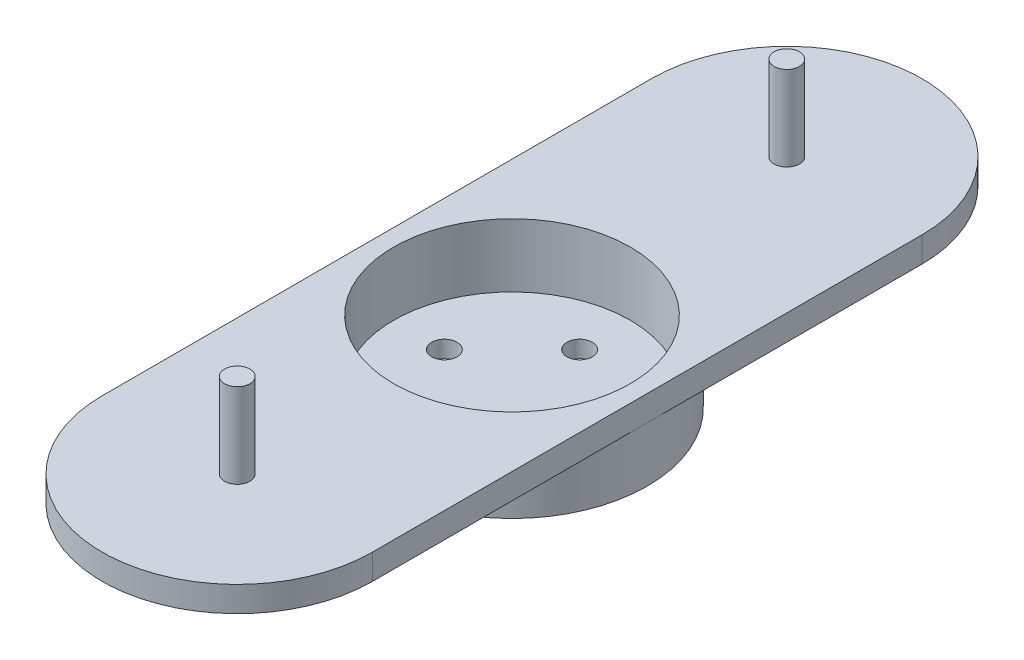
SolidWorks part; units mm, degrees
ref_plane "前视基准面" through (0, 0, 0) normal (0, 0, 1) x (1, 0, 0)
ref_plane "上视基准面" through (0, 0, 0) normal (0, 1, 0) x (1, 0, 0)
ref_plane "右视基准面" through (0, 0, 0) normal (1, 0, 0) x (0, 0, -1)
sketch "Sketch1" plane through (0, 0, 0) normal (0, 1, 0) x (1, 0, 0)
  circle A0 centre (0, 0) radius 16
  dimension "D1" = 32
extrude "Boss-Extrude1" add sketch "Sketch1" along normal blind 6.5
sketch "Sketch2" plane through (0, 6.5, 0) normal (0, 1, 0) x (1, 0, 0)
  line L0 (0, -32.5) -> (0, 32.5) construction
  line L1 (-16, -32.5) -> (-16, 32.5)
  line L2 (16, -32.5) -> (16, 32.5)
  arc A0 (-16, -32.5) -> (16, -32.5) centre (0, -32.5) ccw
  arc A1 (16, 32.5) -> (-16, 32.5) centre (0, 32.5) ccw
  circle A2 centre (0, 0) radius 16 construction
  point P2 (0, 0)
  dimension "D1" = 65
extrude "Boss-Extrude2" add sketch "Sketch2" along normal blind 3
sketch "Sketch3" plane through (0, 9.5, 0) normal (0, 1, 0) x (1, 0, 0)
  circle A0 centre (0, 32.5) radius 1.5
  circle A1 centre (0, -32.5) radius 1.5
  dimension "D1" = 3
extrude "Boss-Extrude3" add sketch "Sketch3" along normal blind 10
sketch "Sketch4" plane through (0, 9.5, 0) normal (0, 1, 0) x (1, 0, 0)
  circle A0 centre (0, 0) radius 14
  circle A1 centre (0, 0) radius 16 construction
  dimension "D1" = 2
extrude "Cut-Extrude1" cut sketch "Sketch4" against normal offset from surface (7.5 mm away) 2 up to face at (0, 0, 16)
sketch "Sketch5" plane through (0, 2, 0) normal (0, 1, 0) x (1, 0, 0)
  circle A0 centre (8, 0) radius 3 construction
  circle A1 centre (8, 0) radius 1.5
  circle A2 centre (0, -8) radius 1.5
  circle A3 centre (-8, 0) radius 1.5
  circle A4 centre (0, 8) radius 1.5
  point P3 (-9.129, -1.967)
  point P4 (0, 0)
  point P13 (0, 0)
  dimension "D1" = 8
  dimension "D2" = 3
  dimension "D3" = 6
  dimension "D4" = 4
extrude "Cut-Extrude2" cut sketch "Sketch5" against normal through all
sketch "Sketch6" plane through (0, 0, 0) normal (0, -1, 0) x (1, 0, 0)
  circle A0 centre (0, 0) radius 4.3467
